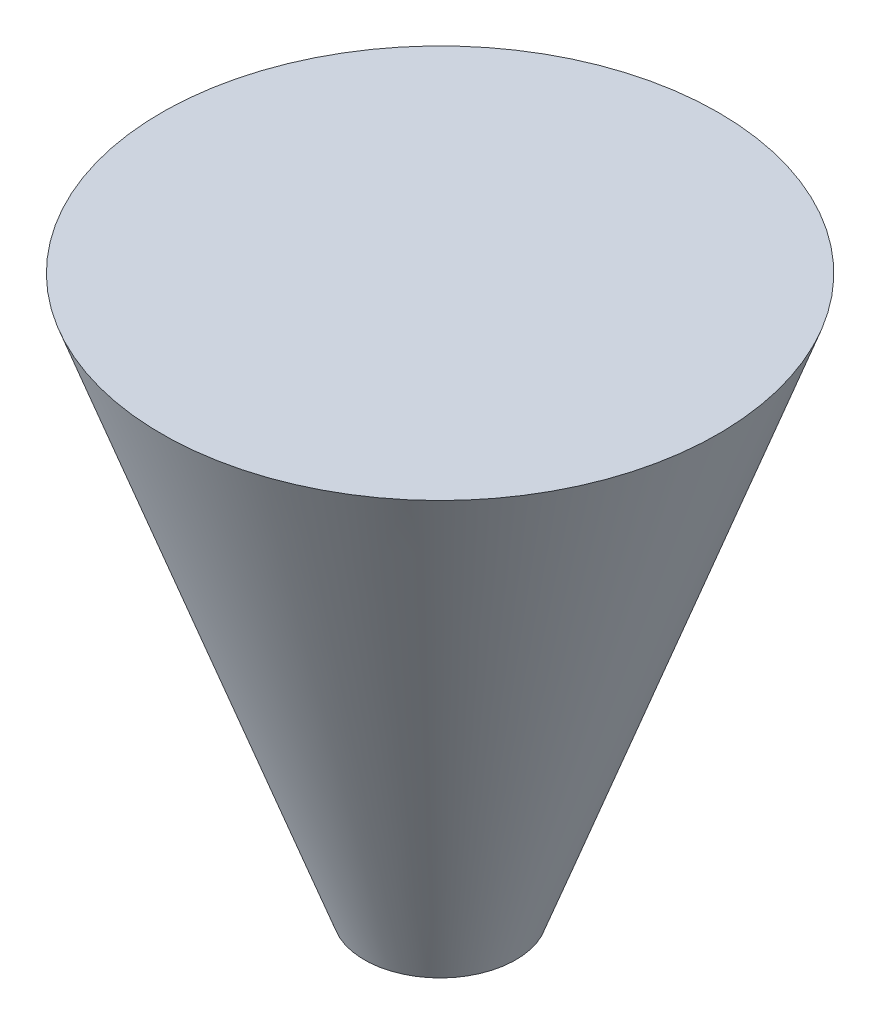
SolidWorks part; units mm, degrees
ref_plane "Plane1" through (0, 0, 0) normal (0, 0, 1) x (1, 0, 0)
ref_plane "Plane2" through (0, 0, 0) normal (0, 1, 0) x (1, 0, 0)
ref_plane "Plane3" through (0, 0, 0) normal (1, 0, 0) x (0, 0, -1)
sketch "Sketch1" plane through (0, 0, 0) normal (0, 0, 1) x (1, 0, 0)
  line L0 (-101.8453, 0) -> (101.8453, 0)
  line L1 (-101.8453, 0) -> (-101.8453, 2)
  line L2 (101.8453, 2) -> (-101.8453, 2)
  line L3 (101.8453, 2) -> (101.8453, 0)
  line L4 (50, 0) -> (-50, 0) construction
  line L5 (0, -25.996) -> (0, 39.4685) construction
  dimension "D1" = 2
extrude "Base-Extrude" add sketch "Sketch1" along normal mid plane 120
sketch "Sketch3" plane through (0, 0, 0) normal (0, -1, 0) x (1, 0, 0)
  circle A0 centre (0, 0) radius 1.5
  dimension "Diameter" = 3
extrude "Boss-Extrude1" add sketch "Sketch3" along normal blind 3 draft 20
sketch "Sketch4" plane through (101.8453, 0, 0) normal (1, 0, 0) x (0, 0, -1)
  line L4 (60, 0) -> (60, 2)
  line L5 (60, 2) -> (-60, 2)
  line L6 (-60, 2) -> (-60, 0)
  line L7 (-60, 0) -> (60, 0)
  line L8 (60, 0) -> (60, 2)
  line L9 (60, 2) -> (-60, 2)
  line L10 (-60, 2) -> (-60, 0)
  line L11 (-60, 0) -> (60, 0)
  dimension "D1" = 0
extrude "Cut-Extrude1" cut sketch "Sketch4" against normal through all
sketch "Orientation sketch" plane through (0, 0, 0) normal (0, 1, 0) x (-1, 0, 0)
  circle A1 centre (0, 0) radius 1.5
  circle A2 centre (0, 0) radius 1.5
  dimension "D1" = 0
